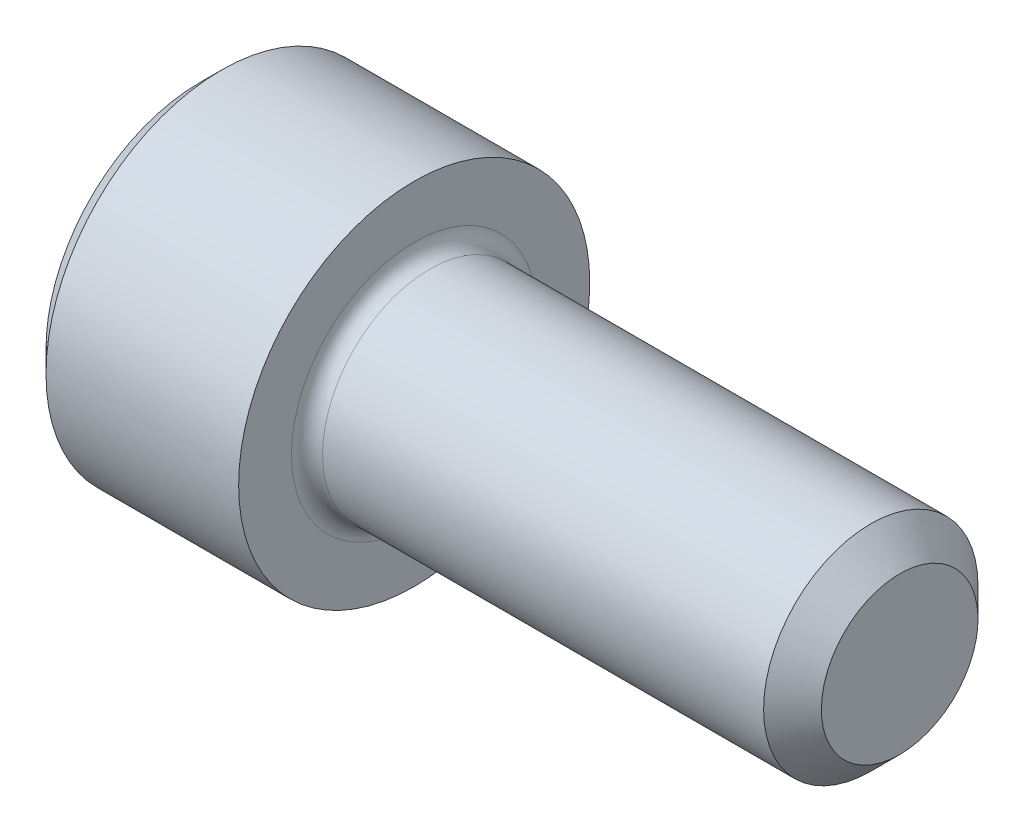
SolidWorks part; units mm, degrees
material "Alloy Steel"
ref_plane "Plane1" through (0, 0, 0) normal (0, 0, 1) x (1, 0, 0)
ref_plane "Plane2" through (0, 0, 0) normal (0, 1, 0) x (1, 0, 0)
ref_plane "Plane3" through (0, 0, 0) normal (1, 0, 0) x (0, 0, -1)
sketch "Sketch1" plane through (0, 0, 0) normal (0, 0, 1) x (1, 0, 0)
  line L0 (-3.5052, 0) -> (-3.5052, 2.8702)
  line L1 (-3.5052, 2.8702) -> (0, 2.8702)
  line L2 (0, 2.8702) -> (0, 1.7526)
  line L3 (0, 1.7526) -> (7.9375, 1.7526)
  line L4 (7.9375, 1.7526) -> (7.9375, 0)
  line L5 (7.9375, 0) -> (-3.5052, 0)
  line L7 (-3.5052, 0) -> (7.9375, 0) construction
  dimension "D1" = 5.7404
  dimension "D2" = 3.5052
  dimension "D3" = 3.5052
  dimension "D4" = 11.4427
revolve "Base-Revolve" add sketch "Sketch1" angle 360 about L5
sketch "Sketch2" plane through (0, 0, 0) normal (0, 0, 1) x (1, 0, 0)
  line L0 (-3.5052, 1.3843) -> (-1.8796, 1.3843)
  line L1 (-1.8796, 1.3843) -> (-1.0804, 0)
  line L2 (-3.5052, 0) -> (7.9375, 0) construction
  line L3 (-1.0804, 0) -> (-3.5052, 0)
  line L4 (-3.5052, 0) -> (-3.5052, 1.3843)
  line L8 (-3.5052, 2.8702) -> (-3.5052, -2.8702) construction
  dimension "D1" = 1.3843
  dimension "D2" = 60
  dimension "D3" = 2.4248
revolve "Hex-PreBroach" cut sketch "Sketch2" angle 360 about axis through (7.9375, 0, 0) along (-1, 0, 0)
sketch "Sketch3" plane through (-3.5052, 0, 0) normal (-1, 0, 0) x (0, 0.5, 0.866)
  line L0 (0.7992, 1.3843) -> (-0.7992, 1.3843)
  line L1 (-0.7992, 1.3843) -> (-1.5985, 0)
  line L2 (0.7992, 1.3843) -> (1.5985, 0)
  line L3 (0.7992, -1.3843) -> (1.5985, 0)
  line L4 (0.7992, -1.3843) -> (-0.7992, -1.3843)
  line L5 (-0.7992, -1.3843) -> (-1.5985, 0)
  dimension "D1" = 1.3843
  dimension "D2" = 1.3843
  dimension "D3" = 2.7686
  dimension "Hex_size" = 2.7686
extrude "Hex" cut sketch "Sketch3" against normal blind 1.6256
fillet "Fillet1" radius 0.254 1 edges at (0, 1.7526, 0)
chamfer "Chamfer1" distance 0.4724 angle 45 1 edges at (7.9375, 1.7526, 0)
chamfer "Chamfer2" distance 0.3556 angle 45 1 edges at (-3.5052, 2.8702, 0)
